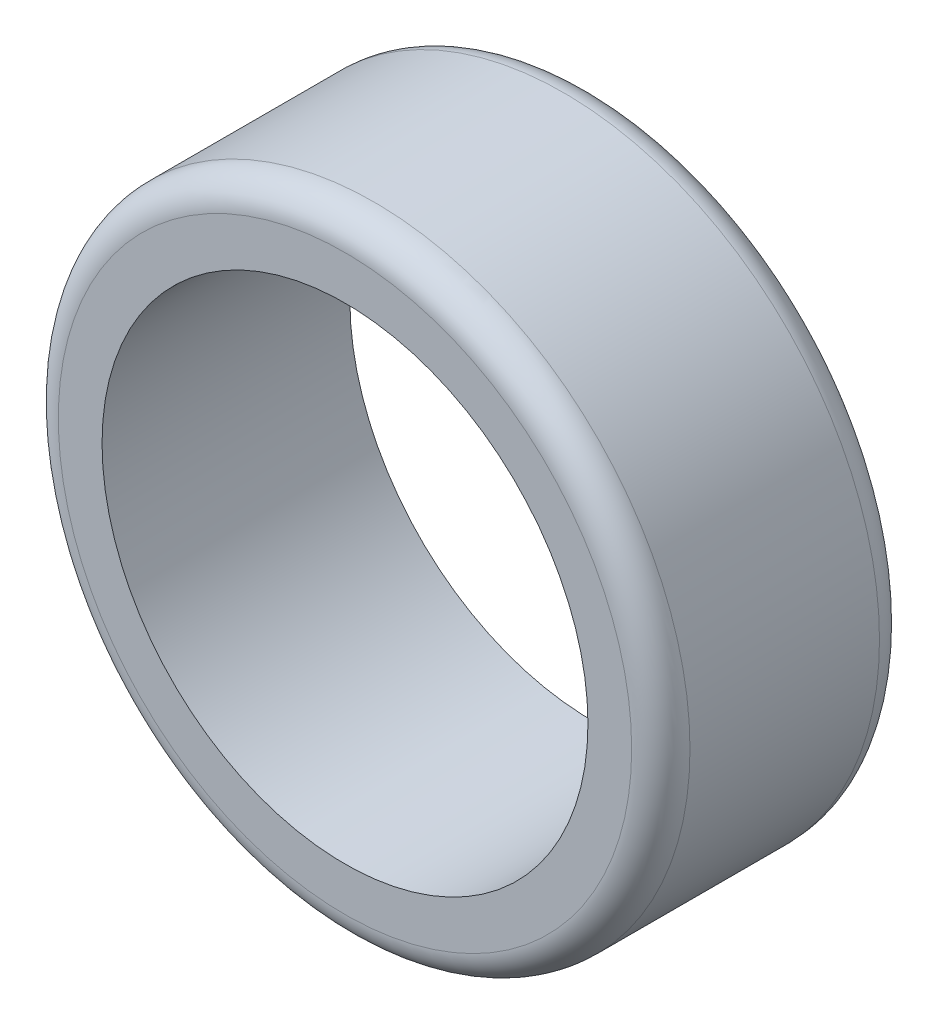
SolidWorks part; units mm, degrees
material "硅橡胶"
ref_plane "前视基准面" through (0, 0, 0) normal (0, 0, 1) x (1, 0, 0)
ref_plane "上视基准面" through (0, 0, 0) normal (0, 1, 0) x (1, 0, 0)
ref_plane "右视基准面" through (0, 0, 0) normal (1, 0, 0) x (0, 0, -1)
sketch "草图1" plane through (0, 0, 0) normal (0, 0, 1) x (1, 0, 0)
  circle A0 centre (0, 0) radius 32.5
extrude "凸台-拉伸1" add sketch "草图1" along normal blind 25.5
sketch "草图2" plane through (0, 0, 25.5) normal (0, 0, 1) x (1, 0, 0)
  circle A0 centre (0, 0) radius 25
extrude "切除-拉伸1" cut sketch "草图2" against normal through all both and the other way through all
fillet "圆角1" radius 3 1 edges at (32.5, 0, 25.5)
fillet "圆角2" radius 3 1 edges at (32.5, 0, 0)
